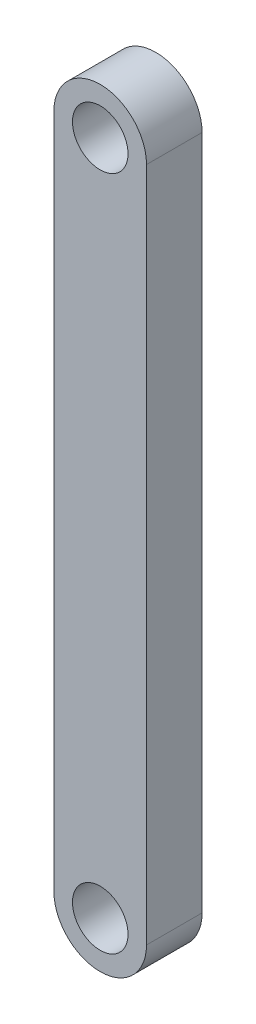
SolidWorks part; units mm, degrees
ref_plane "Front Plane" through (0, 0, 0) normal (0, 0, 1) x (1, 0, 0)
ref_plane "Top Plane" through (0, 0, 0) normal (0, 1, 0) x (1, 0, 0)
ref_plane "Right Plane" through (0, 0, 0) normal (1, 0, 0) x (0, 0, -1)
sketch "Sketch1" plane through (0, 0, 0) normal (0, 0, 1) x (1, 0, 0)
  line L0 (0, 0) -> (0, 365) construction
  line L1 (0, -55) -> (0, 55) construction
  line L2 (-25, 0) -> (-25, 365)
  line L3 (25, 0) -> (25, 365)
  arc A0 (-25, 0) -> (25, 0) centre (0, 0) ccw
  arc A1 (25, 365) -> (-25, 365) centre (0, 365) ccw
  circle A2 centre (0, 365) radius 15
  circle A3 centre (0, 0) radius 15
  point P5 (0, 182.5)
  dimension "D3" = 30
  dimension "D4" = 30
  dimension "D1" = 365
  dimension "D2" = 50
extrude "Boss-Extrude1" add sketch "Sketch1" along normal blind 30
